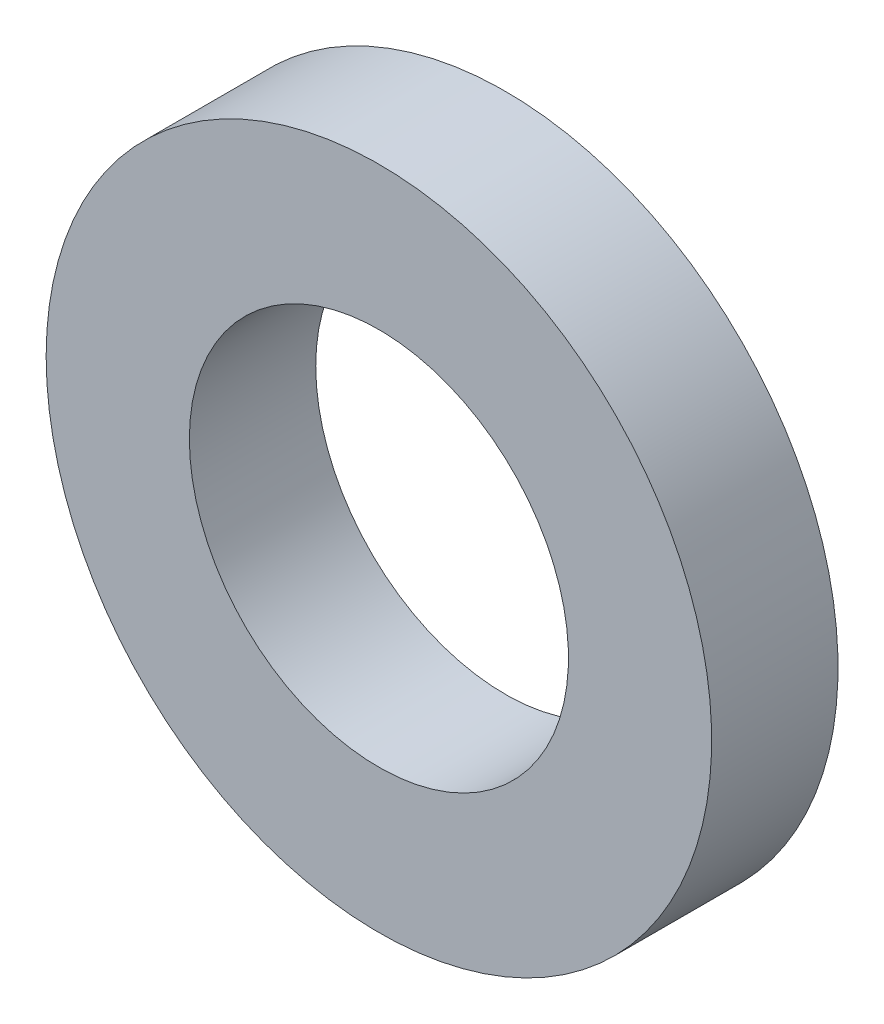
SolidWorks part; units mm, degrees
ref_plane "Спереди" through (0, 0, 0) normal (0, 0, 1) x (1, 0, 0)
ref_plane "Сверху" through (0, 0, 0) normal (0, 1, 0) x (1, 0, 0)
ref_plane "Справа" through (0, 0, 0) normal (1, 0, 0) x (0, 0, -1)
sketch "Sketch1" plane through (0, 0, 0) normal (0, 0, 1) x (1, 0, 0)
  circle A2 centre (0, 0) radius 7.9
  circle A3 centre (0, 0) radius 7.9
  circle A5 centre (0, 0) radius 4.5
  circle A6 centre (0, 0) radius 4.5
  dimension "D1" = 0.1
  dimension "D2" = 0.5
extrude "Extrude1" add sketch "Sketch1" along normal up to surface (3 mm away)
